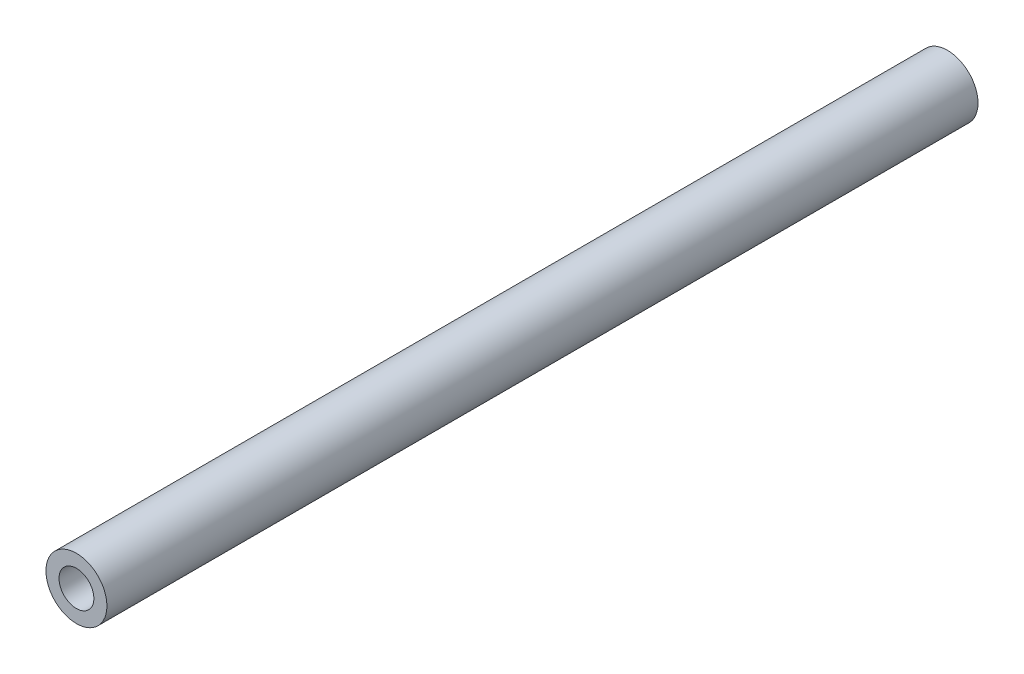
SolidWorks part; units mm, degrees
ref_plane "前视基准面" through (0, 0, 0) normal (0, 0, 1) x (1, 0, 0)
ref_plane "上视基准面" through (0, 0, 0) normal (0, 1, 0) x (1, 0, 0)
ref_plane "右视基准面" through (0, 0, 0) normal (1, 0, 0) x (0, 0, -1)
sketch "草图1" plane through (0, 0, 0) normal (0, 0, 1) x (1, 0, 0)
  circle A0 centre (0, 0) radius 1.75
  circle A1 centre (0, 0) radius 1
  dimension "D1" = 3.5
  dimension "D2" = 2
extrude "凸台-拉伸1" add sketch "草图1" along normal blind 50
